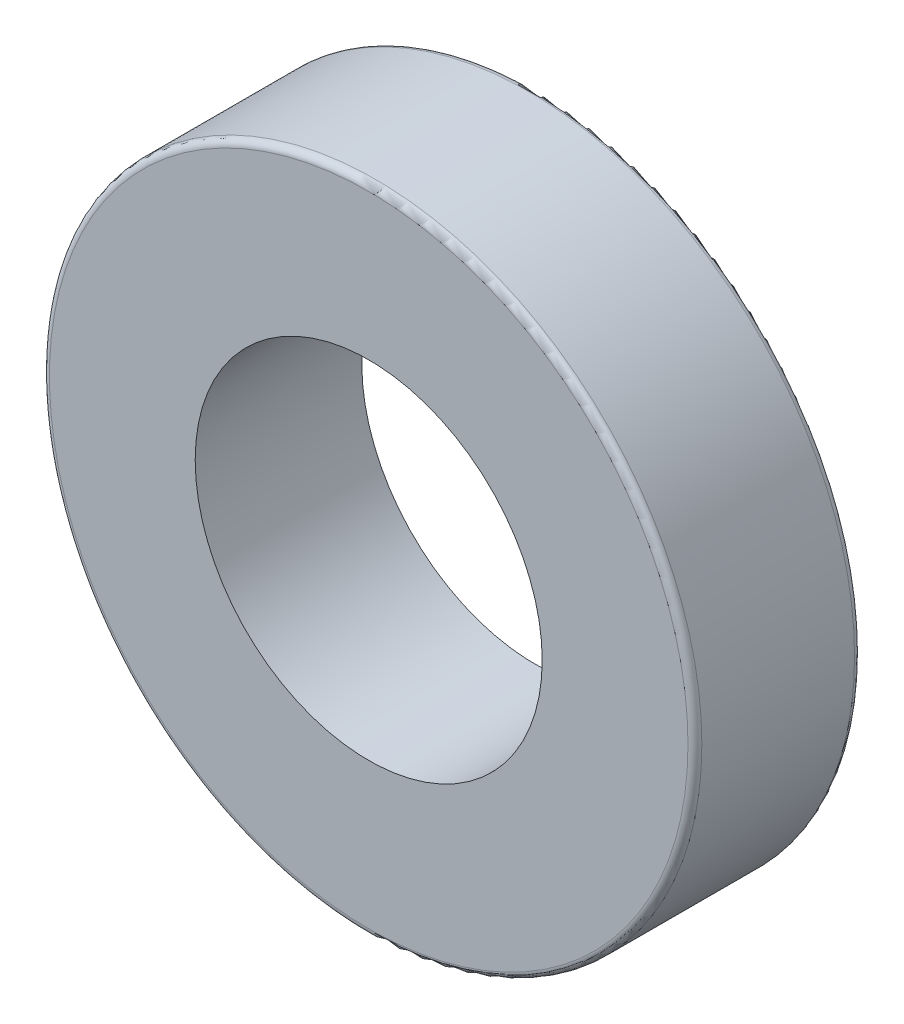
SolidWorks part; units mm, degrees
material "Alloy Steel"
ref_plane "Front Plane" through (0, 0, 0) normal (0, 0, 1) x (1, 0, 0)
ref_plane "Top Plane" through (0, 0, 0) normal (0, 1, 0) x (1, 0, 0)
ref_plane "Right Plane" through (0, 0, 0) normal (1, 0, 0) x (0, 0, -1)
sketch "Sketch2" plane through (0, 0, 0) normal (0, 0, 1) x (1, 0, 0)
  circle A0 centre (0, 0) radius 23.5
  circle A1 centre (0, 0) radius 12.5
extrude "Boss-Extrude1" add sketch "Sketch2" along normal blind 12
fillet "Fillet1" radius 0.5 2 edges at (23.5, 0, 0) (23.5, 0, 12)
